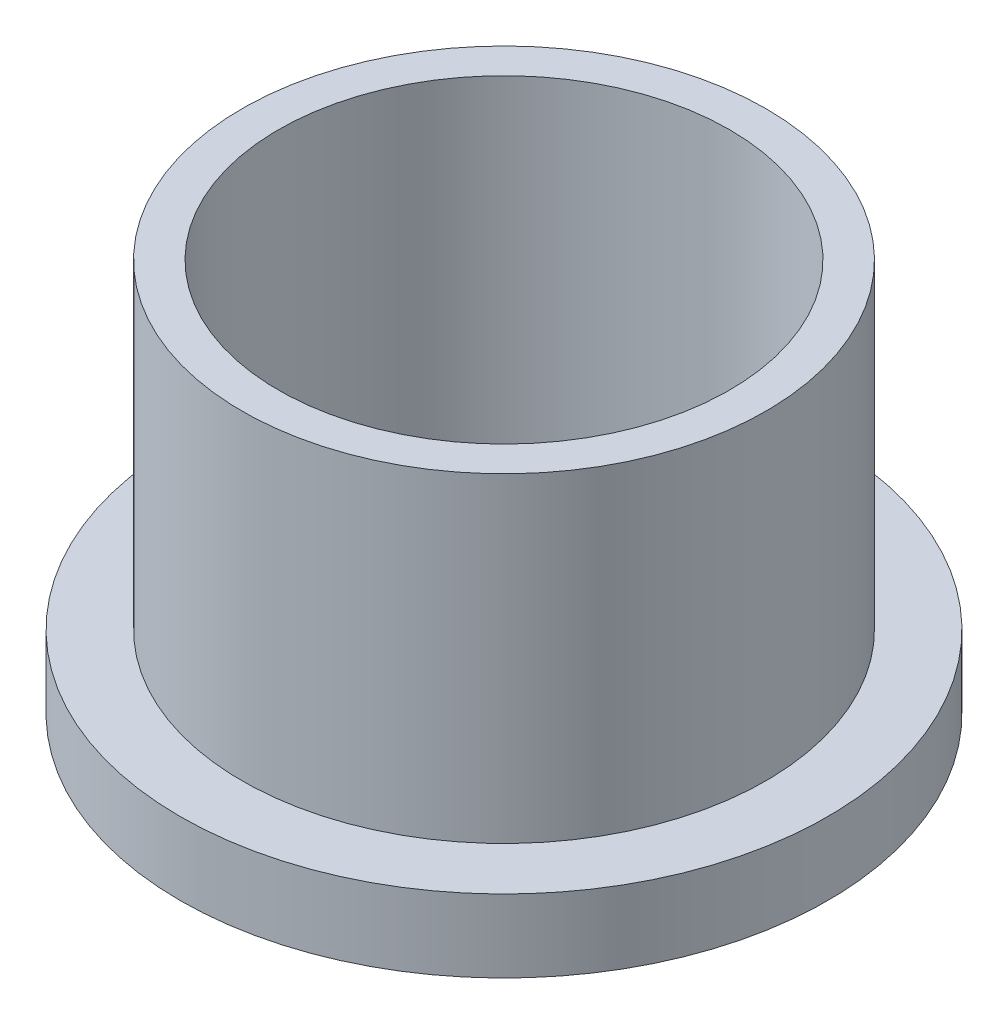
SolidWorks part; units mm, degrees
material "Brass"
ref_plane "Front Plane" through (0, 0, 0) normal (0, 0, 1) x (1, 0, 0)
ref_plane "Top Plane" through (0, 0, 0) normal (0, 1, 0) x (1, 0, 0)
ref_plane "Right Plane" through (0, 0, 0) normal (1, 0, 0) x (0, 0, -1)
sketch "Sketch1" plane through (0, 0, 0) normal (0, 0, 1) x (1, 0, 0)
  line L0 (0, 0) -> (0, 34409.7443) construction
  line L1 (0, 0) -> (-34409.7443, 0) construction
  line L2 (31, 0) -> (44.5, 0)
  line L3 (44.5, 0) -> (44.5, 10)
  line L4 (44.5, 10) -> (36, 10)
  line L5 (36, 10) -> (36, 54)
  line L6 (36, 54) -> (31, 54)
  line L7 (31, 54) -> (31, 0)
  dimension "D1" = 13.5
  dimension "D2" = 10
  dimension "D3" = 8.5
  dimension "D4" = 44
  dimension "D5" = 5
  dimension "D6" = 31
revolve "Revolve1" add sketch "Sketch1" angle 360 about L0
